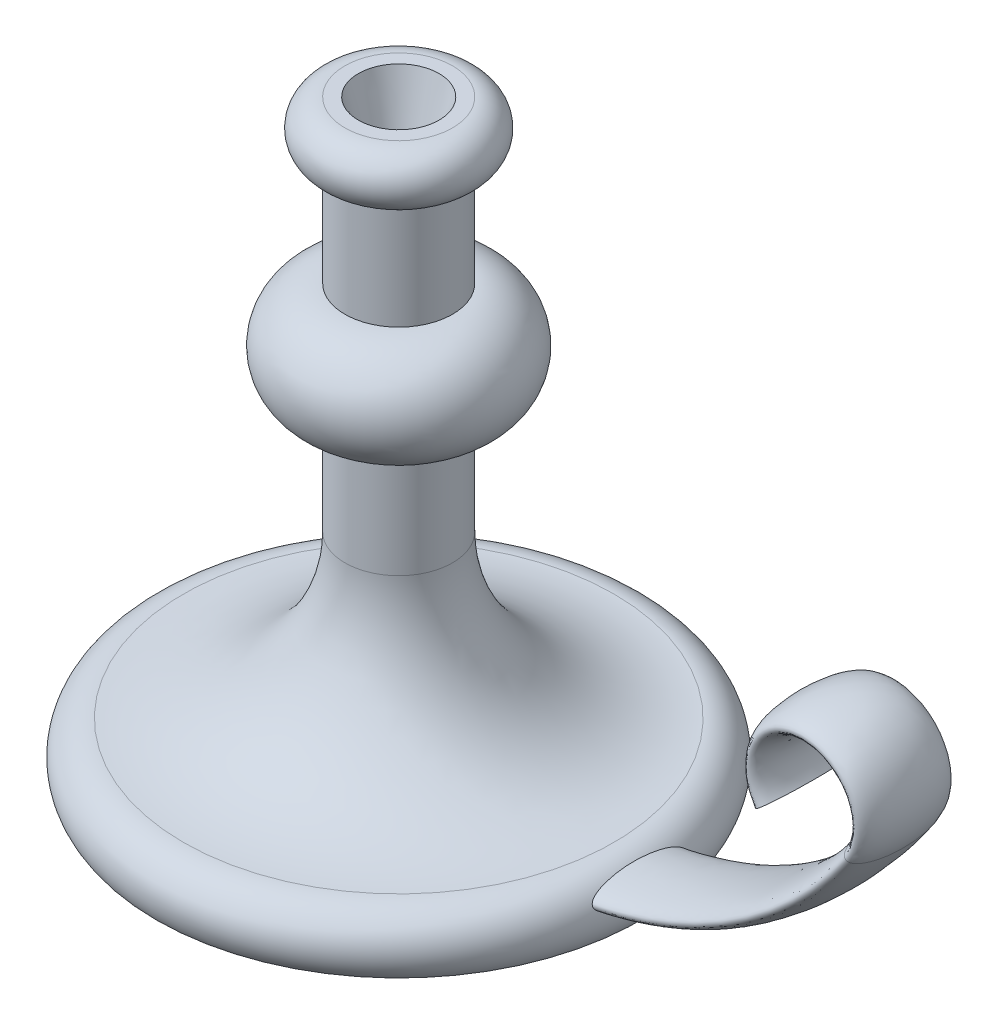
SolidWorks part; units mm, degrees
ref_plane "Front Plane" through (0, 0, 0) normal (0, 0, 1) x (1, 0, 0)
ref_plane "Top Plane" through (0, 0, 0) normal (0, 1, 0) x (1, 0, 0)
ref_plane "Right Plane" through (0, 0, 0) normal (1, 0, 0) x (0, 0, -1)
sketch "Sketch1" plane through (0, 0, 0) normal (0, 0, 1) x (1, 0, 0)
  line L0 (0, 0) -> (0, 220)
  line L1 (20, 220) -> (0, 220)
  line L2 (0, 0) -> (90, 0)
  line L3 (20, 200) -> (20, 160)
  line L4 (20, 120) -> (20, 80)
  arc A0 (20, 220) -> (20, 200) centre (20, 210) cw
  arc A1 (20, 160) -> (20, 120) centre (20, 140) cw
  arc A2 (20, 80) -> (80, 20) centre (80, 80) ccw
  arc A3 (80, 20) -> (90, 0) centre (80, 7.5) cw
  dimension "D4" = 10
  dimension "D5" = 20
  dimension "D7" = 60
  dimension "D9" = 12.5
  dimension "D1" = 220
  dimension "D2" = 20
  dimension "D3" = 90
  dimension "D6" = 40
  dimension "D8" = 80
revolve "Revolve1" add sketch "Sketch1" angle 360 about L0
sketch "Sketch2" plane through (0, 0, 0) normal (0, 0, 1) x (1, 0, 0)
  line L0 (0, 10) -> (60, 10)
  line L1 (0, 200) -> (0, 160) construction
  line L2 (0, 164) -> (0, 92) construction
  line L3 (-90, 0) -> (90, 0) construction
  arc A0 (60, 10) -> (183.5921, 75) centre (60, 160) ccw
  arc A1 (183.5921, 75) -> (150.6342, 75) centre (167.1131, 86.3333) ccw
  point P10 (0, 0)
  dimension "D2" = 150
  dimension "D4" = 20
  dimension "D1" = 60
  dimension "D3" = 65
  dimension "D5" = 10
sketch "Sketch3" plane through (0, 0, 0) normal (1, 0, 0) x (0, 0, -1)
  ellipse E0 centre (0, 10) end of major axis (17.5, 10) minor radius 5
  dimension "D1" = 35
  dimension "D2" = 10
sweep "Sweep1" add profiles "Sketch3" path "Sketch2"
sketch "Sketch4" plane through (0, 220, 0) normal (0, 1, 0) x (1, 0, 0)
  circle A0 centre (0, 0) radius 15
  dimension "D1" = 30
extrude "Cut-Extrude1" cut sketch "Sketch4" against normal blind 25 draft 15
